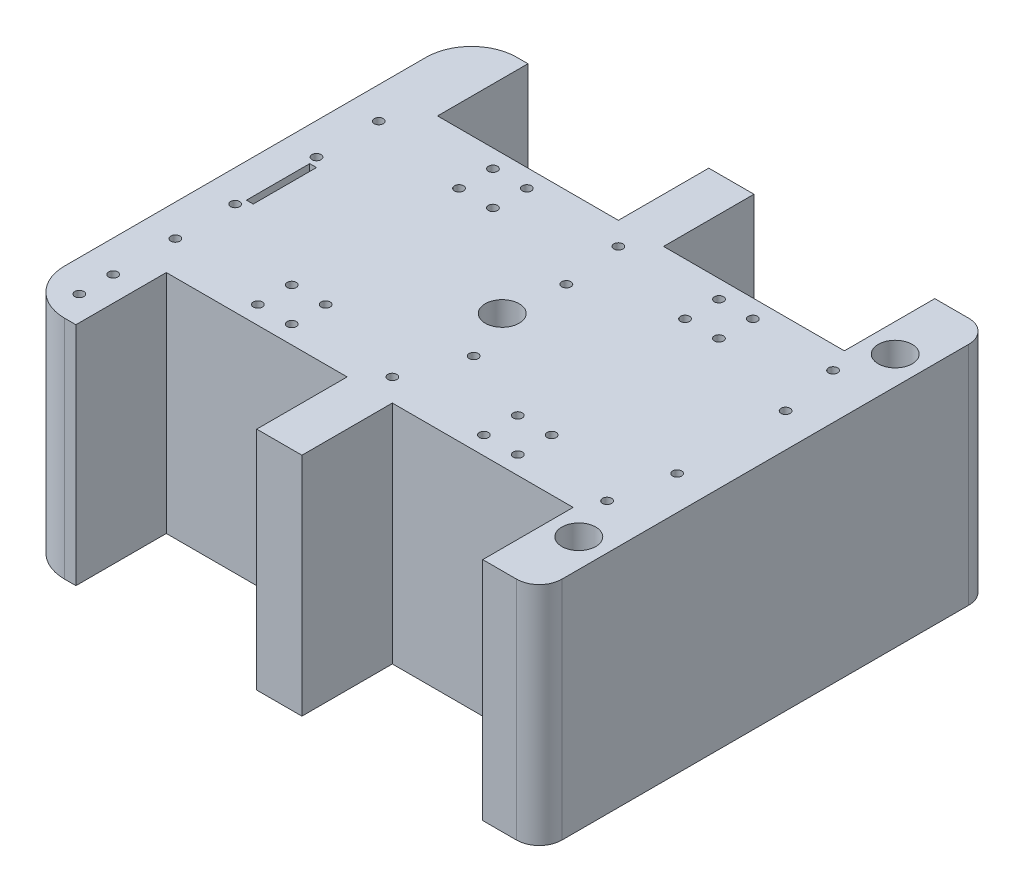
SolidWorks part; units mm, degrees
ref_plane "Alzado" through (0, 0, 0) normal (0, 0, 1) x (1, 0, 0)
ref_plane "Planta" through (0, 0, 0) normal (0, 1, 0) x (1, 0, 0)
ref_plane "Vista lateral" through (0, 0, 0) normal (1, 0, 0) x (0, 0, -1)
sketch "Croquis1" plane through (0, 0, 0) normal (0, 1, 0) x (1, 0, 0)
  line L0 (0, 0) -> (0, 40)
  line L1 (0, 40) -> (80, 40)
  line L2 (100, 40) -> (100, 0)
  line L3 (100, 0) -> (80, 0)
  line L4 (80, 0) -> (80, 40)
  line L6 (180, 40) -> (180, 0)
  line L10 (180, 200) -> (180, 160)
  line L11 (180, 160) -> (100, 160)
  line L12 (100, 160) -> (100, 200)
  line L13 (100, 200) -> (80, 200)
  line L14 (80, 200) -> (80, 160)
  line L15 (80, 160) -> (0, 160)
  line L16 (0, 160) -> (0, 200)
  line L19 (-5, 0) -> (0, 0)
  line L20 (180, 200) -> (195, 200)
  line L21 (205, 190) -> (205, 10)
  line L22 (0, 0) -> (-5, 0)
  line L23 (-25, 20) -> (-25, 180)
  line L24 (-5, 200) -> (0, 200)
  line L25 (100, 40) -> (180, 40)
  line L26 (180, 0) -> (195, 0)
  line L27 (40, 160) -> (40, 27.7716) construction
  line L28 (-10, 113.45) -> (-7, 113.45)
  line L29 (-10, 113.45) -> (-10, 85.45)
  line L30 (-10, 85.45) -> (-7, 85.45)
  line L31 (-7, 113.45) -> (-7, 85.45)
  line L32 (140, 160) -> (140, 40) construction
  line L33 (-25, 100) -> (205, 100) construction
  arc A4 (195, 200) -> (205, 190) centre (195, 190) cw
  arc A5 (205, 10) -> (195, 0) centre (195, 10) cw
  arc A6 (-5, 0) -> (-25, 20) centre (-5, 20) cw
  arc A7 (-25, 180) -> (-5, 200) centre (-5, 180) cw
  circle A8 centre (-5, 70) radius 7.5
  circle A9 centre (-5, 130) radius 7.5
  circle A10 centre (192.5, 170) radius 7.5
  circle A11 centre (192.5, 30) radius 7.5
  circle A12 centre (90, 98.6178) radius 7.5
  circle A14 centre (32.5, 152) radius 2
  circle A15 centre (47.5, 152) radius 2
  circle A16 centre (47.5, 137) radius 2
  circle A17 centre (32.5, 137) radius 2
  circle A18 centre (32.5, 48) radius 2
  circle A19 centre (32.5, 63) radius 2
  circle A20 centre (47.5, 48) radius 2
  circle A21 centre (47.5, 63) radius 2
  circle A22 centre (132.5, 152) radius 2
  circle A23 centre (132.5, 137) radius 2
  circle A24 centre (147.5, 152) radius 2
  circle A25 centre (147.5, 137) radius 2
  circle A26 centre (132.5, 63) radius 2
  circle A27 centre (132.5, 48) radius 2
  circle A28 centre (147.5, 63) radius 2
  circle A29 centre (147.5, 48) radius 2
  circle A30 centre (90, 150) radius 2
  circle A31 centre (90, 50) radius 2
  circle A32 centre (185, 50) radius 2
  circle A34 centre (185, 150) radius 2
  circle A35 centre (90, 150) radius 2
  point P25 (205, 0)
  point P51 (40, 160)
  point P74 (140, 160)
  dimension "D1" = 40
  dimension "D2" = 25
  dimension "D3" = 200
  dimension "D9" = 10
  dimension "D10" = 20
  dimension "D11" = 20
  dimension "D12" = 12.5
  dimension "D19" = 15
  dimension "D17" = 15
  dimension "D24" = 8
  dimension "D25" = 15
  dimension "D27" = 15
  dimension "D29" = 8
  dimension "D31" = 15
  dimension "D35" = 10
  dimension "D36" = 10
  dimension "D37" = 20
  dimension "D4" = 120
  dimension "D5" = 80
  dimension "D6" = 80
  dimension "D7" = 20
  dimension "D8" = 40
  dimension "D13" = 20
  dimension "D14" = 60
  dimension "D15" = 30
  dimension "D16" = 12.5
  dimension "D18" = 30
  dimension "D20" = 90
  dimension "D21" = 25
  dimension "D22" = 98.6178
  dimension "D23" = 40
  dimension "D26" = 7.5
  dimension "D28" = 15
  dimension "D30" = 15
  dimension "D32" = 15
  dimension "D33" = 7.5
  dimension "D34" = 7.5
extrude "Saliente-Extruir1" add sketch "Croquis1" against normal blind 100 contours A7 L23 A6 L19 L0 L1 L4 L3 L2 L25 L6 L26 A5 L21 A4 L20 L10 L11 L12 L13 L14 L15 L16 L24 A12 A11 A10 A9 A8
sketch "Croquis2" plane through (0, 0, 0) normal (0, 1, 0) x (1, 0, 0)
  circle A0 centre (-5, 130) radius 7.5
  circle A1 centre (-5, 70) radius 7.5
extrude "Saliente-Extruir2" add sketch "Croquis2" against normal blind 115
sketch "Croquis3" plane through (0, 0, 0) normal (0, 1, 0) x (1, 0, 0)
  line L0 (0, 40) -> (0, 20) construction
  line L2 (0, 0) -> (0, 40) construction
  line L3 (95, 124) -> (93, 124) construction
  line L5 (102, 76) -> (100, 76) construction
  line L6 (190, 122) -> (190, 124) construction
  line L7 (190, 78) -> (190, 76) construction
  line L8 (190, 76) -> (188, 76) construction
  line L9 (190, 124) -> (188, 124) construction
  circle A2 centre (-11, 117.45) radius 2
  circle A3 centre (-11, 81.45) radius 2
  circle A4 centre (190, 76) radius 2
  circle A5 centre (-12.5, 25.7298) radius 2
  circle A6 centre (-12.5, 10.7298) radius 2
  circle A8 centre (190, 124) radius 2
  circle A9 centre (93, 124) radius 2
  circle A10 centre (100, 76) radius 2
  dimension "D1" = 15
  dimension "D4" = 90
  dimension "D5" = 97
extrude "Cortar-Extruir2" cut sketch "Croquis3" against normal blind 149
sketch "Croquis4" plane through (0, 0, 0) normal (0, 1, 0) x (1, 0, 0)
  circle A0 centre (-12.5, 25.7298) radius 2
  circle A1 centre (-12.5, 10.7298) radius 2
extrude "Saliente-Extruir3" add sketch "Croquis4" against normal blind 86
sketch "Croquis5" plane through (0, 0, 0) normal (0, 1, 0) x (1, 0, 0)
  line L0 (0, 40) -> (-9, 40) construction
  circle A0 centre (-11, 40) radius 2
  circle A1 centre (-11, 25) radius 2
  dimension "D1" = 15
extrude "Cortar-Extruir3" cut sketch "Croquis5" against normal blind 139
sketch "Croquis7" plane through (0, 0, 0) normal (0, 1, 0) x (1, 0, 0)
  circle A0 centre (-11, 145) radius 2
  circle A1 centre (-11, 55) radius 2
  dimension "D1" = 90
extrude "Cortar-Extruir4" cut sketch "Croquis7" against normal blind 139
sketch "Croquis8" plane through (0, 0, 0) normal (0, 1, 0) x (1, 0, 0)
  circle A0 centre (-11, 40) radius 2
  circle A1 centre (-11, 25) radius 2
extrude "Saliente-Extruir4" add sketch "Croquis8" against normal blind 78
sketch "Croquis9" plane through (0, 0, 0) normal (0, 1, 0) x (1, 0, 0)
  line L1 (-25, 20) -> (-25, 180) construction
  line L2 (0, 0) -> (0, 40) construction
  line L3 (0, 40) -> (0, 27.5) construction
  line L4 (0, 27.5) -> (-11, 27.5) construction
  circle A0 centre (-11, 27.5) radius 2
  circle A1 centre (-11, 12.5) radius 2
  dimension "D1" = 15
  dimension "D2" = 14
extrude "Cortar-Extruir5" cut sketch "Croquis9" against normal blind 117
